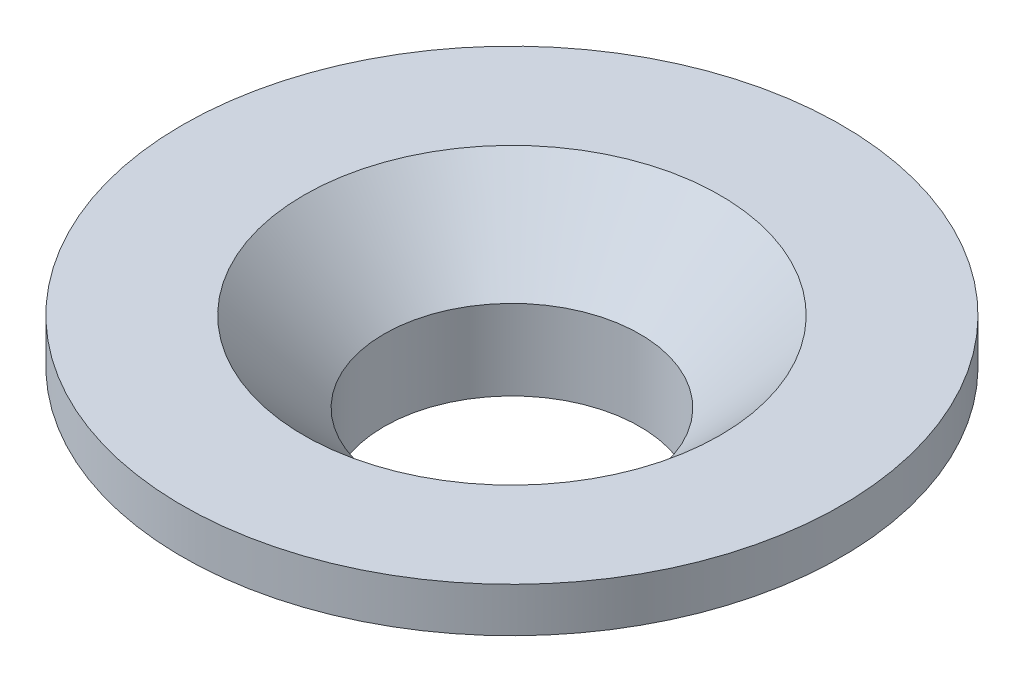
SolidWorks part; units mm, degrees
ref_plane "Płaszczyzna przednia" through (0, 0, 0) normal (0, 0, 1) x (1, 0, 0)
ref_plane "Płaszczyzna górna" through (0, 0, 0) normal (0, 1, 0) x (1, 0, 0)
ref_plane "Płaszczyzna prawa" through (0, 0, 0) normal (1, 0, 0) x (0, 0, -1)
sketch "Sketch1" plane through (0, 0, 0) normal (0, 0, 1) x (1, 0, 0)
  line L1 (0, 5) -> (6.82, 5)
  line L2 (6.82, 5) -> (6.82, 2.5)
  line L5 (-11.68, 6.1336) -> (-11.68, -4.0668)
  line L10 (0, 5) -> (-4.5, 0.5)
  line L11 (-2.5, 0) -> (-2.5, -4)
  line L12 (-4.5, 0.5) -> (-4.5, -4)
  line L13 (-4.5, -4) -> (-2.5, -4)
  line L14 (0, 2.5) -> (6.82, 2.5)
  circle A2 centre (0, 0) radius 2.5
  point P8 (0, 0)
  point P11 (0, 0)
  dimension "D8" = 4
  dimension "D6" = 4.5
  dimension "D2" = 5
  dimension "D3" = 18.5
  dimension "D4" = 2.5
  dimension "D7" = 135
  dimension "D11" = 2
  dimension "7.18" = 7.18
revolve "Revolve1" add sketch "Sketch1" angle 360 about L5
